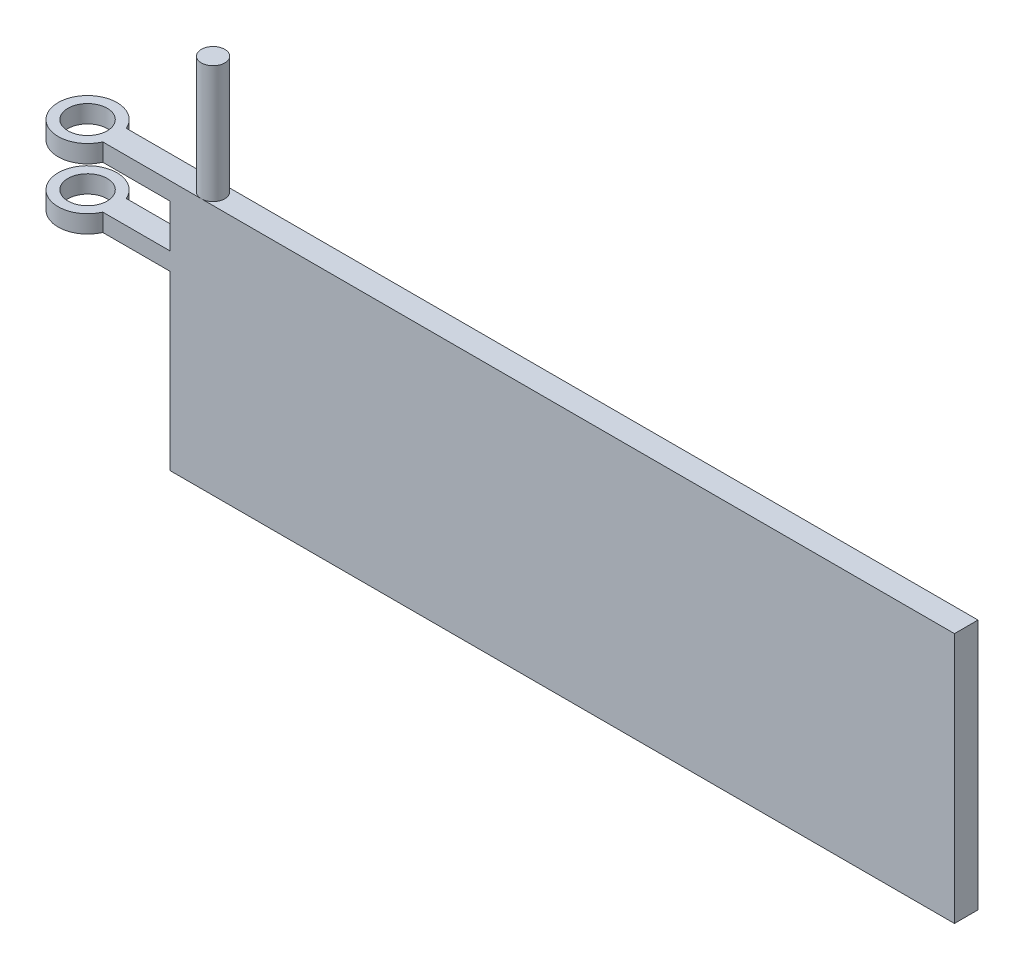
SolidWorks part; units mm, degrees
ref_plane "Front Plane" through (0, 0, 0) normal (0, 0, 1) x (1, 0, 0)
ref_plane "Top Plane" through (0, 0, 0) normal (0, 1, 0) x (1, 0, 0)
ref_plane "Right Plane" through (0, 0, 0) normal (1, 0, 0) x (0, 0, -1)
sketch "Sketch2" plane through (0, 0, 0) normal (0, 1, 0) x (1, 0, 0)
  line L1 (-50, 1.5) -> (50, 1.5)
  line L2 (-50, 1.5) -> (-50, -1.5)
  line L3 (-50, -1.5) -> (50, -1.5)
  line L4 (50, 1.5) -> (50, -1.5)
  line L5 (-50, 1.5) -> (50, -1.5) construction
  line L6 (-50, -1.5) -> (50, 1.5) construction
  point P0 (0, 0)
  dimension "D1" = 3
  dimension "D2" = 100
extrude "Boss-Extrude1" add sketch "Sketch2" along normal blind 22
sketch "Sketch3" plane through (0, 22, 0) normal (0, 1, 0) x (1, 0, 0)
  line L0 (-50, 1.5) -> (-50, -1.5) construction
  line L1 (50, 1.5) -> (-58.5631, 1.5)
  line L2 (50, 1.5) -> (50, -1.5)
  line L3 (50, -1.5) -> (-58.5631, -1.5)
  line L5 (-50, 0) -> (-62, 0) construction
  circle A0 centre (-62, 0) radius 2.5
  arc A1 (-58.5631, 1.5) -> (-58.5631, -1.5) centre (-62, 0) ccw
  dimension "D2" = 5
  dimension "D3" = 7.5
  dimension "D1" = 12
extrude "Boss-Extrude2" add sketch "Sketch3" along normal blind 10
sketch "Sketch4" plane through (0, 32, 0) normal (0, 1, 0) x (1, 0, 0)
  line L0 (-62, 0) -> (-46, 0) construction
  circle A0 centre (-46, 0) radius 1.5
  dimension "D1" = 16
extrude "Boss-Extrude3" add sketch "Sketch4" along normal blind 15
sketch "Sketch5" plane through (0, 0, 1.5) normal (0, 0, 1) x (1, 0, 0)
  line L0 (-50, 22) -> (-50, 32) construction
  line L1 (-58.5631, 32) -> (-46, 32) construction
  line L2 (-50, 27) -> (-65.75, 27) construction
  line L3 (-65.75, 32) -> (-65.75, 22) construction
  line L4 (-65.75, 27) -> (-65.75, 24.25)
  line L5 (-65.75, 27) -> (-65.75, 29.75)
  line L6 (-65.75, 32) -> (-65.75, 22) construction
  line L7 (-65.75, 29.75) -> (-50, 29.75)
  line L8 (-65.75, 24.25) -> (-50, 24.25)
  line L9 (-50, 29.75) -> (-50, 24.25)
  point P12 (-65.75, 35.6561)
  dimension "D1" = 2.75
  dimension "D2" = 10
extrude "Cut-Extrude1" cut sketch "Sketch5" against normal through all both and the other way through all
